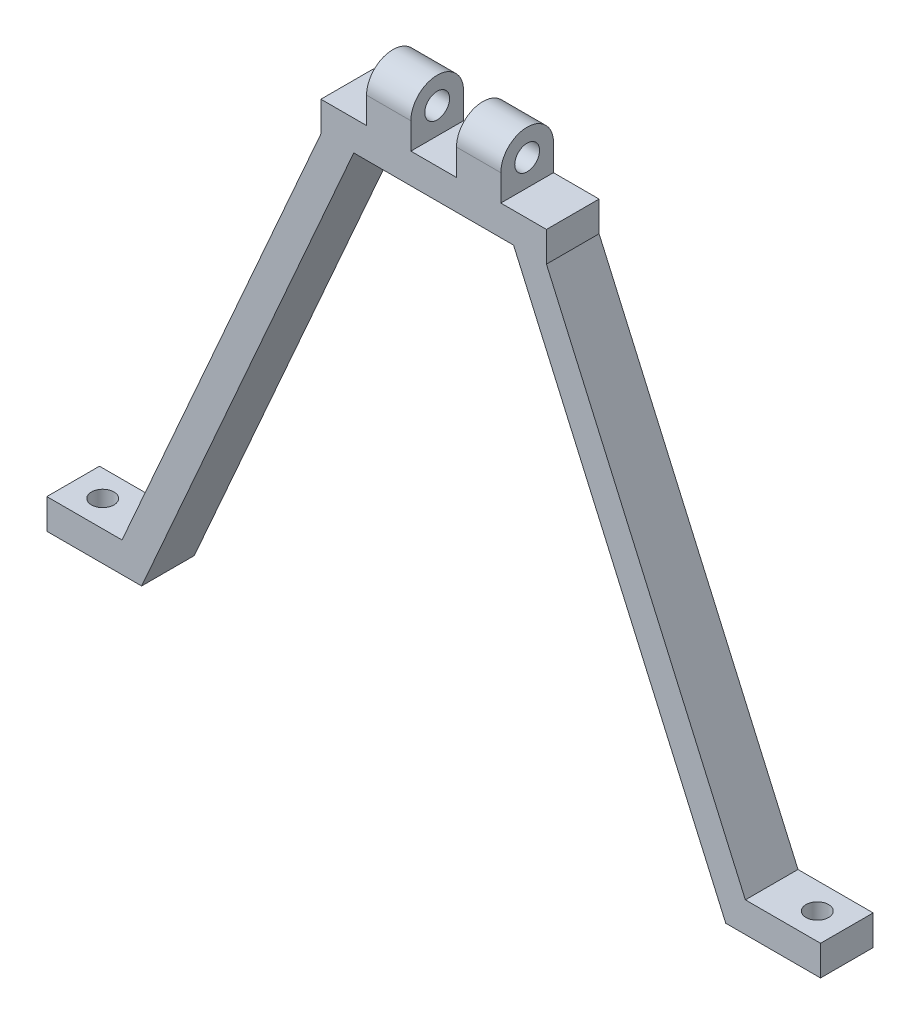
SolidWorks part; units mm, degrees
ref_plane "Front Plane" through (0, 0, 0) normal (0, 0, 1) x (1, 0, 0)
ref_plane "Top Plane" through (0, 0, 0) normal (0, 1, 0) x (1, 0, 0)
ref_plane "Right Plane" through (0, 0, 0) normal (1, 0, 0) x (0, 0, -1)
sketch "Croquis4" plane through (0, 0, 0) normal (0, 0, 1) x (1, 0, 0)
  line L0 (51.455, 0) -> (-51.455, 0)
  line L1 (51.455, -4) -> (-51.455, -4)
  line L2 (-51.455, -4) -> (-51.455, 0)
  line L3 (51.455, -4) -> (51.455, 0)
  line L4 (-15, -4) -> (-41.455, -64)
  line L5 (-41.455, -64) -> (-51.455, -64)
  line L6 (-51.455, -64) -> (-51.455, -68)
  line L7 (-51.455, -68) -> (-38.8471, -68)
  line L8 (-38.8471, -68) -> (-10.6284, -4)
  line L9 (0, 0) -> (0, -4) construction
  line L10 (15, -4) -> (41.455, -64)
  line L11 (38.8471, -68) -> (10.6284, -4)
  line L12 (51.455, -68) -> (38.8471, -68)
  line L13 (51.455, -64) -> (51.455, -68)
  line L14 (41.455, -64) -> (51.455, -64)
  point P4 (0, 0)
  dimension "D1" = 102.91
  dimension "D3" = 4
  dimension "D4" = 4
  dimension "D5" = 60
  dimension "D6" = 15
  dimension "D7" = 10
  dimension "D2" = 4
extrude "Saliente-Extruir3" add sketch "Croquis4" along normal blind 7 contours L7 L8 L1 L4 L5 L6 | L9 L0 L2 L1 | L0 L9 L1 L3 | L14 L10 L1 L11 L12 L13
sketch "Croquis5" plane through (0, 0, 0) normal (0, 1, 0) x (1, 0, 0)
  line L0 (-51.455, -7) -> (-51.455, 0) construction
  circle A0 centre (-47.525, -3.5) radius 1.5
  circle A1 centre (47.525, -3.5) radius 1.5
  point P4 (0, 0)
  point P8 (-51.455, -3.5)
  point P9 (-47.525, -3.5)
  point P10 (47.525, -3.5)
  point P11 (-47.525, -3.5)
  dimension "D3" = 3
  dimension "D1" = 95.05
  dimension "D2" = 47.525
extrude "Cortar-Extruir2" cut sketch "Croquis5" against normal through all and the other way through all
sketch "Croquis6" plane through (0, 0, 0) normal (1, 0, 0) x (0, 0, -1)
  line L0 (-7, 0) -> (0, 0) construction
  line L1 (-3.5, 3.5) -> (0, 3.5) construction
  line L3 (-7, 3.5) -> (-7, 0)
  line L4 (-7, 0) -> (0, 0)
  line L5 (0, 0) -> (0, 3.5)
  circle A0 centre (-3.5, 3.5) radius 3.5
  circle A1 centre (-3.5, 3.5) radius 1.65
  dimension "D1" = 7
  dimension "D2" = 3.3
extrude "Saliente-Extruir4" add sketch "Croquis6" along normal mid plane 30
sketch "Croquis7" plane through (0, 0, 7) normal (0, 0, 1) x (1, 0, 0)
  line L0 (15, 7) -> (-15, 7) construction
  line L1 (-15, 0) -> (-8.93, 0)
  line L2 (-15, 0) -> (-15, 7)
  line L3 (-15, 7) -> (-8.93, 7)
  line L4 (-8.93, 0) -> (-8.93, 7)
  line L5 (-15, 7) -> (-15, 3.5) construction
  line L6 (-15, 0) -> (-51.455, 0) construction
  line L7 (15, 0) -> (8.93, 0)
  line L8 (15, 0) -> (15, 7)
  line L9 (15, 7) -> (8.93, 7)
  line L10 (8.93, 0) -> (8.93, 7)
  line L11 (-3.035, 0) -> (3.035, 0)
  line L12 (-3.035, 0) -> (-3.035, 7)
  line L13 (-3.035, 7) -> (3.035, 7)
  line L14 (3.035, 0) -> (3.035, 7)
  point P17 (0, 0)
  dimension "D1" = 6.07
  dimension "D2" = 6.07
  dimension "D3" = 6.07
extrude "Cortar-Extruir3" cut sketch "Croquis7" against normal through all
sketch "Croquis8" plane through (0, 0, 7) normal (0, 0, 1) x (1, 0, 0)
  line L1 (-15, -4) -> (-51.455, -4)
  line L2 (-15, -4) -> (-15, 0)
  line L3 (-15, 0) -> (-51.455, 0)
  line L4 (-51.455, -4) -> (-51.455, 0)
  line L5 (15, -4) -> (51.455, -4)
  line L6 (15, -4) -> (15, 0)
  line L7 (15, 0) -> (51.455, 0)
  line L8 (51.455, -4) -> (51.455, 0)
extrude "Cortar-Extruir4" cut sketch "Croquis8" against normal through all
